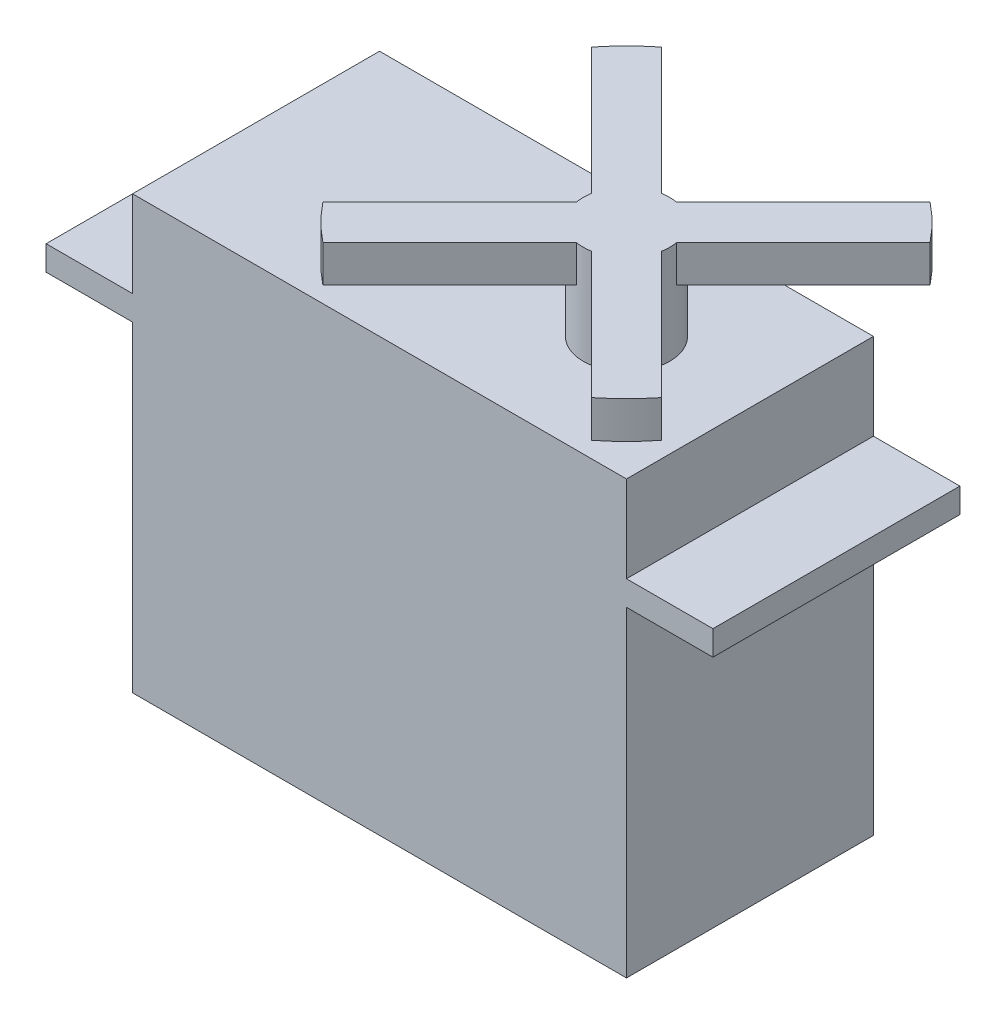
SolidWorks part; units mm, degrees
ref_plane "Plan de face" through (0, 0, 0) normal (0, 0, 1) x (1, 0, 0)
ref_plane "Plan de dessus" through (0, 0, 0) normal (0, 1, 0) x (1, 0, 0)
ref_plane "Plan de droite" through (0, 0, 0) normal (1, 0, 0) x (0, 0, -1)
sketch "Esquisse1" plane through (0, 0, 0) normal (0, 0, 1) x (1, 0, 0)
  line L0 (-21.8081, -11.6436) -> (-21.8081, 14.3564)
  line L1 (-21.8081, 23.3564) -> (18.1919, 23.3564)
  line L2 (-21.8081, 14.3564) -> (-28.8081, 14.3564)
  line L3 (-21.8081, -11.6436) -> (18.1919, -11.6436)
  line L4 (-28.8081, 14.3564) -> (-28.8081, 16.3564)
  line L5 (-28.8081, 16.3564) -> (-21.8081, 16.3564)
  line L6 (-21.8081, 16.3564) -> (-21.8081, 23.3564)
  line L7 (18.1919, 23.3564) -> (18.1919, 16.3564)
  line L8 (18.1919, 16.3564) -> (25.1919, 16.3564)
  line L9 (25.1919, 16.3564) -> (25.1919, 14.3564)
  line L10 (25.1919, 14.3564) -> (18.1919, 14.3564)
  line L11 (18.1919, 14.3564) -> (18.1919, -11.6436)
  dimension "D1" = 40
  dimension "D2" = 35
  dimension "D3" = 7
  dimension "D4" = 7
  dimension "D5" = 2
  dimension "D6" = 26
extrude "Extrusion1" add sketch "Esquisse1" along normal blind 20
sketch "Esquisse2" plane through (0, 23.3564, 0) normal (0, 1, 0) x (1, 0, 0)
  line L0 (18.1919, -20) -> (18.1919, 0) construction
  line L1 (18.1919, 0) -> (-21.8081, 0) construction
  circle A0 centre (8.1919, -10) radius 3.5
  dimension "D3" = 7
  dimension "D1" = 10
  dimension "D2" = 10
extrude "Extrusion2" add sketch "Esquisse2" along normal blind 8
sketch "Esquisse3" plane through (0, 31.3564, 0) normal (0, 1, 0) x (1, 0, 0)
  line L0 (4.7467, -9.3832) -> (-5.5156, 0.8791)
  line L1 (7.5751, -6.5548) -> (-2.6872, 3.7075)
  line L2 (4.7467, -9.3832) -> (7.5751, -6.5548) construction
  line L3 (8.8087, -6.5548) -> (19.0698, 3.7063)
  line L4 (11.6371, -9.3832) -> (21.8982, 0.8779)
  line L5 (8.8087, -6.5548) -> (11.6371, -9.3832) construction
  line L6 (4.7467, -10.6168) -> (-5.5156, -20.8791)
  line L7 (4.7467, -10.6168) -> (7.5751, -13.4452) construction
  line L8 (-2.6872, -23.7075) -> (7.5751, -13.4452)
  line L9 (8.8087, -13.4452) -> (19.071, -23.7075)
  line L11 (21.8994, -20.8791) -> (11.6371, -10.6168)
  line L12 (8.1919, 10.3386) -> (8.1919, -36.1899) construction
  arc A0 (-5.5156, 0.8791) -> (-2.6872, 3.7075) centre (8.1919, -10) cw
  circle A1 centre (8.1919, -10) radius 3.5 construction
  arc A2 (19.0698, 3.7063) -> (21.8982, 0.8779) centre (8.1919, -10) cw
  circle A3 centre (8.1919, -10) radius 3.5 construction
  arc A4 (-2.6872, -23.7075) -> (-5.5156, -20.8791) centre (8.1919, -10) cw
  arc A5 (21.8994, -20.8791) -> (19.071, -23.7075) centre (8.1919, -10) cw
  arc A6 (7.5751, -6.5548) -> (8.8087, -6.5548) centre (8.1919, -10) cw
  arc A7 (11.6371, -9.3832) -> (11.6371, -10.6168) centre (8.1919, -10) cw
  arc A8 (8.8087, -13.4452) -> (7.5751, -13.4452) centre (8.1919, -10) cw
  arc A9 (4.7467, -10.6168) -> (4.7467, -9.3832) centre (8.1919, -10) cw
  dimension "D1" = 17.5
  dimension "D4" = 17.4983
  dimension "D5" = 17.5
  dimension "D6" = 17.5
  dimension "D2" = 4
  dimension "D3" = 4
  dimension "D7" = 4
  dimension "D8" = 45
extrude "Extrusion3" add sketch "Esquisse3" against normal blind 3
